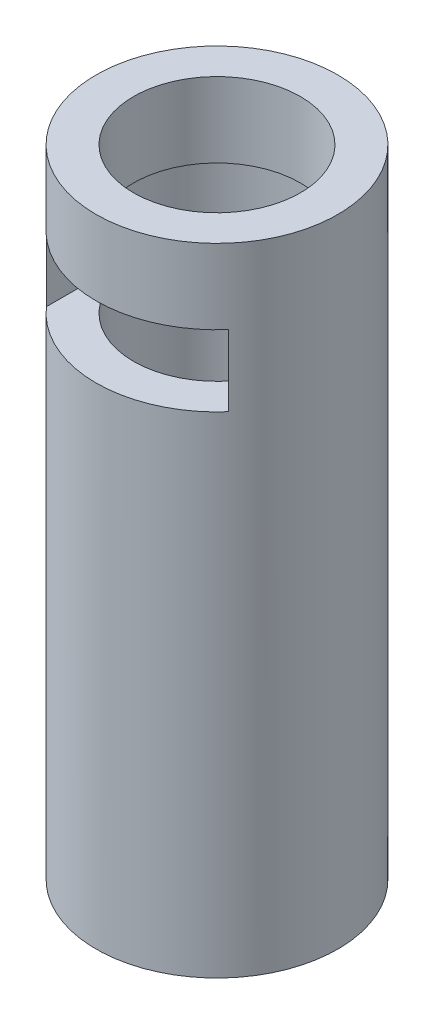
SolidWorks part; units mm, degrees
ref_plane "Front" through (0, 0, 0) normal (0, 0, 1) x (1, 0, 0)
ref_plane "Top" through (0, 0, 0) normal (0, 1, 0) x (1, 0, 0)
ref_plane "Right" through (0, 0, 0) normal (1, 0, 0) x (0, 0, -1)
sketch "Sketch1" plane through (0, 0, 0) normal (0, 1, 0) x (1, 0, 0)
  circle A0 centre (0, 0) radius 11.15
  circle A1 centre (0, 0) radius 16.15
  dimension "D1" = 22.3
  dimension "D2" = 5
extrude "Boss-Extrude1" add sketch "Sketch1" along normal blind 80
sketch "Sketch2" plane through (0, 0, 0) normal (0, -1, 0) x (1, 0, 0)
  circle A0 centre (0, 0) radius 9.15
  circle A1 centre (0, 0) radius 16.15
  circle A2 centre (0, 0) radius 16.15
  dimension "D1" = 0
  dimension "D2" = 7
extrude "Boss-Extrude2" add sketch "Sketch2" along normal blind 5
ref_plane "Plane2" through (0, 70, 0) normal (0, 1, 0) x (1, 0, 0)
sketch "Sketch4" plane through (0, 70, 0) normal (0, 1, 0) x (1, 0, 0)
  line L0 (0, -16.15) -> (0, -12.15) construction
  line L1 (-12.15, 0) -> (-12.15, -18.1268)
  line L2 (12.15, 0) -> (12.15, -18.1268)
  line L3 (12.15, -18.1268) -> (-12.15, -18.1268)
  line L5 (0, 12.15) -> (0, 16.15) construction
  circle A0 centre (0, 0) radius 16.15 construction
  circle A3 centre (0, 0) radius 12.15
  arc A4 (12.15, 0) -> (-12.15, 0) centre (0, 0) ccw
  dimension "D1" = 1
extrude "Cut-Extrude1" cut sketch "Sketch4" against normal blind 9.5
